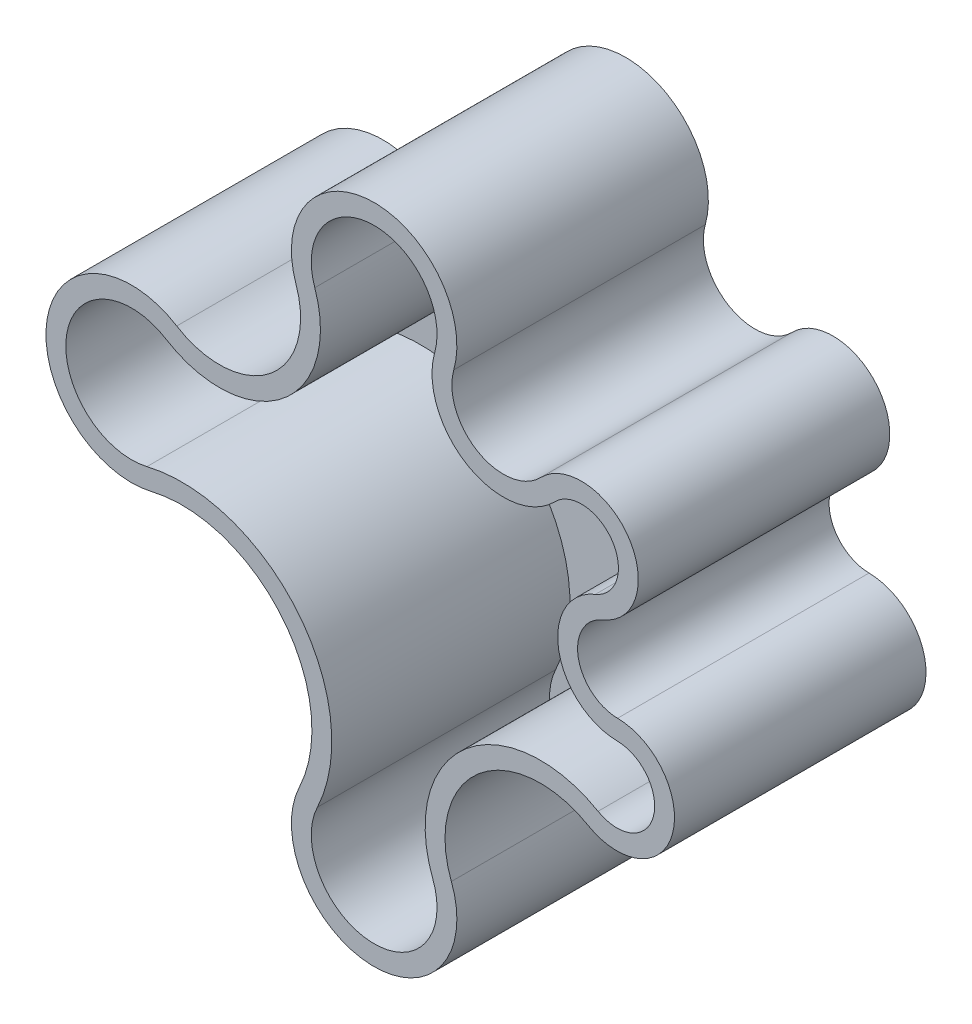
SolidWorks part; units mm, degrees
ref_plane "Front Plane" through (0, 0, 0) normal (0, 0, 1) x (1, 0, 0)
ref_plane "Top Plane" through (0, 0, 0) normal (0, 1, 0) x (1, 0, 0)
ref_plane "Right Plane" through (0, 0, 0) normal (1, 0, 0) x (0, 0, -1)
sketch "Sketch1" plane through (0, 0, 0) normal (0, 0, 1) x (1, 0, 0)
  circle A0 centre (0, 0) radius 37.5
  circle A1 centre (0, 37.5) radius 12.5
  circle A2 centre (19.5426, 32.0053) radius 7.8004
  circle A3 centre (0, -37.5) radius 12.5
  circle A4 centre (-23.3638, 29.3323) radius 12.2503
  circle A5 centre (-36.6508, 7.9352) radius 12.9366
  circle A6 centre (25.1275, -27.8363) radius 14.4218
  circle A7 centre (-29.035, -23.7323) radius 19.6338
  circle A8 centre (36.6789, -7.8043) radius 8.7021
  circle A9 centre (36.8404, 7.0023) radius 6.1054
  circle A10 centre (31.3237, 20.6174) radius 8.5849
  dimension "D1" = 75
  dimension "D2" = 25
extrude "Boss-Extrude2" add sketch "Sketch1" along normal blind 2 contours A10 A2 A1 A4 A5 A7 A3 A6 A8 A9 | A0 A1 | A0 A1 | A0 A5 | A5 A0 | A0 A3 | A0 A3 | A0 A8 | A0 A8 | A0 A10 | A0 A10
sketch "Sketch2" plane through (0, 0, 2) normal (0, 0, 1) x (1, 0, 0)
  arc A0 (-31.4089, 16.3767) -> (-8.9678, 34.365) centre (-23.3638, 29.3323) ccw
  arc A1 (9.1454, 34.9286) -> (-8.9678, 34.365) centre (0, 37.5) ccw
  arc A2 (9.1454, 34.9286) -> (27.3081, 24.4989) centre (19.5426, 32.0053) ccw
  arc A3 (33.421, 15.4412) -> (27.3081, 24.4989) centre (31.3237, 20.6174) ccw
  arc A4 (33.421, 15.4412) -> (36.7411, -2.1025) centre (36.8404, 7.0023) ccw
  arc A5 (33.8305, -12.744) -> (36.7411, -2.1025) centre (36.6789, -7.8043) ccw
  arc A6 (33.8305, -12.744) -> (8.8669, -34.0899) centre (25.1275, -27.8363) ccw
  arc A7 (-8.5839, -33.4297) -> (8.8669, -34.0899) centre (0, -37.5) ccw
  arc A8 (-8.5839, -33.4297) -> (-34.3274, -1.7259) centre (-29.035, -23.7323) ccw
  arc A9 (-31.4089, 16.3767) -> (-34.3274, -1.7259) centre (-36.6508, 7.9352) ccw
  arc A10 (34.5476, 12.6608) -> (36.7738, 0.8973) centre (36.8404, 7.0023) ccw
  arc A11 (34.5476, 12.6608) -> (25.1511, 26.584) centre (31.3237, 20.6174) ccw
  arc A12 (12.0334, 34.1166) -> (25.1511, 26.584) centre (19.5426, 32.0053) ccw
  arc A13 (12.0334, 34.1166) -> (-11.7997, 33.3749) centre (0, 37.5) ccw
  arc A14 (-29.8263, 18.9253) -> (-11.7997, 33.3749) centre (-23.3638, 29.3323) ccw
  arc A15 (-29.8263, 18.9253) -> (-33.6259, -4.6428) centre (-36.6508, 7.9352) ccw
  arc A16 (-11.2946, -32.1444) -> (-33.6259, -4.6428) centre (-29.035, -23.7323) ccw
  arc A17 (-11.2946, -32.1444) -> (11.6669, -33.013) centre (0, -37.5) ccw
  arc A18 (32.3318, -15.3428) -> (11.6669, -33.013) centre (25.1275, -27.8363) ccw
  arc A19 (32.3318, -15.3428) -> (36.7738, 0.8973) centre (36.6789, -7.8043) ccw
  arc A20 (34.5476, 12.6608) -> (36.7738, 0.8973) centre (36.8404, 7.0023) ccw
  arc A21 (34.5476, 12.6608) -> (25.1511, 26.584) centre (31.3237, 20.6174) ccw
  arc A22 (12.0334, 34.1166) -> (25.1511, 26.584) centre (19.5426, 32.0053) ccw
  arc A23 (12.0334, 34.1166) -> (-11.7997, 33.3749) centre (0, 37.5) ccw
  arc A24 (-29.8263, 18.9253) -> (-11.7997, 33.3749) centre (-23.3638, 29.3323) ccw
  arc A25 (-29.8263, 18.9253) -> (-33.6259, -4.6428) centre (-36.6508, 7.9352) ccw
  arc A26 (-11.2946, -32.1444) -> (-33.6259, -4.6428) centre (-29.035, -23.7323) ccw
  arc A27 (-11.2946, -32.1444) -> (11.6669, -33.013) centre (0, -37.5) ccw
  arc A28 (32.3318, -15.3428) -> (11.6669, -33.013) centre (25.1275, -27.8363) ccw
  arc A29 (32.3318, -15.3428) -> (36.7738, 0.8973) centre (36.6789, -7.8043) ccw
  dimension "D1" = 0
  dimension "D2" = 3
extrude "Boss-Extrude3" add sketch "Sketch2" along normal blind 36
